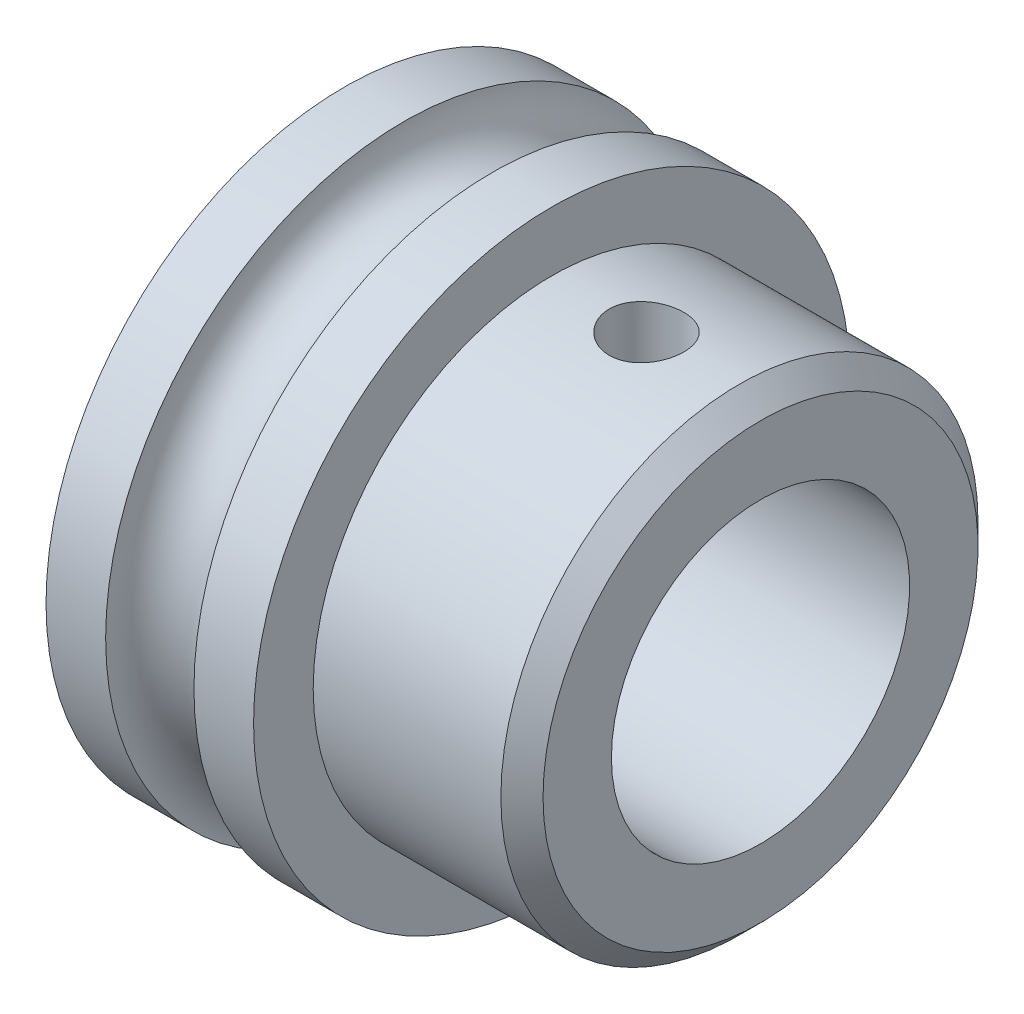
SolidWorks part; units mm, degrees
ref_plane "Front Plane" through (0, 0, 0) normal (0, 0, 1) x (1, 0, 0)
ref_plane "Top Plane" through (0, 0, 0) normal (0, 1, 0) x (1, 0, 0)
ref_plane "Right Plane" through (0, 0, 0) normal (1, 0, 0) x (0, 0, -1)
sketch "Sketch1" plane through (0, 0, 0) normal (0, 1, 0) x (1, 0, 0)
  line L0 (-8.8646, 3.175) -> (0, 3.175)
  line L1 (0, 3.175) -> (0, 4.631)
  line L2 (0, 4.631) -> (-0.449, 5.08)
  line L3 (-0.449, 5.08) -> (-4.445, 5.08)
  line L4 (-10.922, 0) -> (0, 0) construction
  line L5 (-5.715, 6.35) -> (-4.445, 6.35)
  line L6 (-4.445, 6.35) -> (-4.445, 5.08)
  line L7 (-7.5946, 6.35) -> (-8.8646, 6.35)
  line L9 (-8.8646, 6.35) -> (-8.8646, 3.175)
  arc A0 (-5.715, 6.35) -> (-7.5946, 6.35) centre (-6.6548, 6.35) cw
  dimension "D2" = 12.7
  dimension "D3" = 0.9398
  dimension "D1" = 6.35
  dimension "D4" = 10.16
  dimension "D5" = 4.445
  dimension "D6" = 1.27
  dimension "D7" = 0.635
  dimension "D8" = 45
revolve "Revolve1" add sketch "Sketch1" angle 360 about L4
sketch "Sketch2" plane through (0, 0, 0) normal (0, 1, 0) x (1, 0, 0)
  circle A0 centre (-2.4272, 0) radius 0.7937
  dimension "D1" = 1.5875
extrude "Cut-Extrude1" cut sketch "Sketch2" along normal through all
